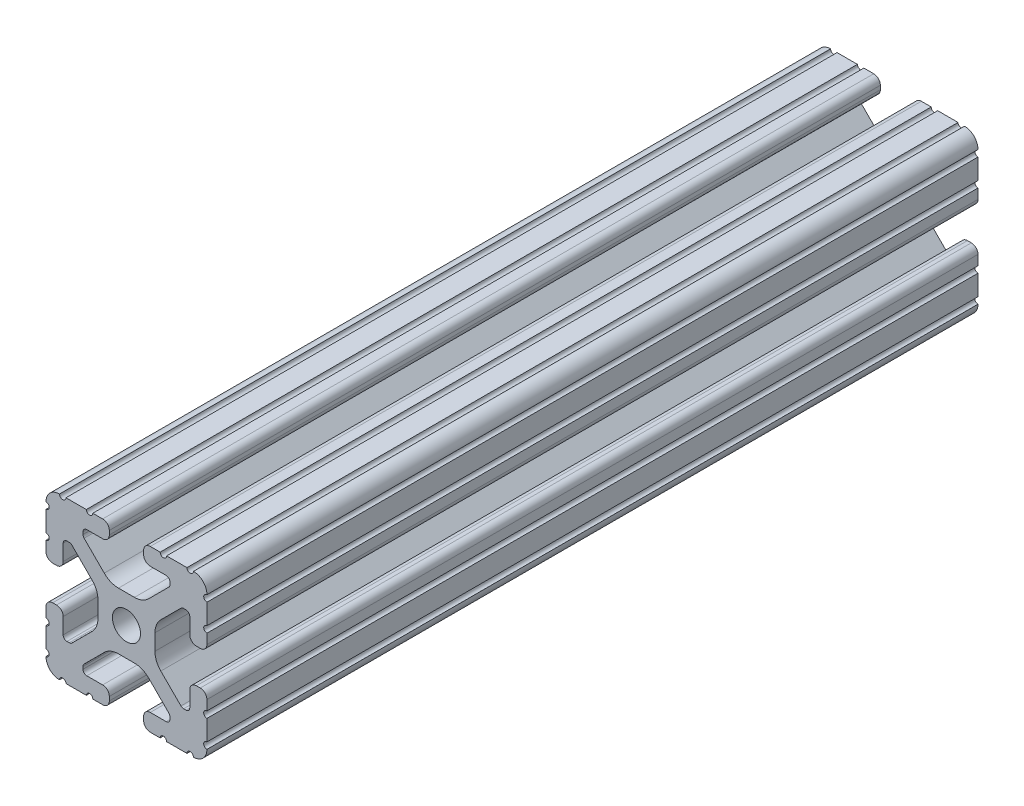
SolidWorks part; units mm, degrees
material "6105-T5 Aluminum"
ref_plane "Front Plane" through (0, 0, 0) normal (0, 0, 1) x (1, 0, 0)
ref_plane "Top Plane" through (0, 0, 0) normal (0, 1, 0) x (1, 0, 0)
ref_plane "Right Plane" through (0, 0, 0) normal (1, 0, 0) x (0, 0, -1)
sketch "Sketch1" plane through (0, 0, 0) normal (0, 0, 1) x (1, 0, 0)
  line L0 (-14.097, 10.287) -> (-13.5289, 10.287)
  line L1 (-12.9003, 10.0266) -> (-8.1292, 5.2555)
  line L2 (-6.738, 1.8969) -> (-6.738, -1.8969)
  line L3 (-8.1292, -5.2555) -> (-12.9003, -10.0266)
  line L4 (-13.5289, -10.287) -> (-14.097, -10.287)
  line L5 (-14.986, -9.398) -> (-14.986, -5.6388)
  line L6 (-16.5608, -4.064) -> (-17.4752, -4.064)
  line L7 (-19.05, -5.6388) -> (-19.05, -7.9756)
  line L8 (-19.05, -9.4996) -> (-19.05, -14.3256)
  line L9 (-19.05, -15.8496) -> (-19.05, -15.875)
  line L10 (-15.875, -19.05) -> (-15.8496, -19.05)
  line L11 (-14.3256, -19.05) -> (-9.4996, -19.05)
  line L12 (-7.9756, -19.05) -> (-5.6388, -19.05)
  line L13 (-4.064, -17.4752) -> (-4.064, -16.5608)
  line L14 (-5.6388, -14.986) -> (-9.398, -14.986)
  line L15 (-10.287, -14.097) -> (-10.287, -13.5289)
  line L16 (-10.0266, -12.9003) -> (-5.2555, -8.1292)
  line L17 (-1.8969, -6.738) -> (1.8969, -6.738)
  line L18 (5.2555, -8.1292) -> (10.0266, -12.9003)
  line L19 (10.287, -13.5289) -> (10.287, -14.097)
  line L20 (9.398, -14.986) -> (5.6388, -14.986)
  line L21 (4.064, -16.5608) -> (4.064, -17.4752)
  line L22 (5.6388, -19.05) -> (7.9756, -19.05)
  line L23 (9.4996, -19.05) -> (14.3256, -19.05)
  line L24 (15.8496, -19.05) -> (15.875, -19.05)
  line L25 (19.05, -15.875) -> (19.05, -15.8496)
  line L26 (19.05, -14.3256) -> (19.05, -9.4996)
  line L27 (19.05, -7.9756) -> (19.05, -5.6388)
  line L28 (17.4752, -4.064) -> (16.5608, -4.064)
  line L29 (14.986, -5.6388) -> (14.986, -9.398)
  line L30 (14.097, -10.287) -> (13.5289, -10.287)
  line L31 (12.9003, -10.0266) -> (8.1292, -5.2555)
  line L32 (6.738, -1.8969) -> (6.738, 1.8969)
  line L33 (8.1292, 5.2555) -> (12.9003, 10.0266)
  line L34 (13.5289, 10.287) -> (14.097, 10.287)
  line L35 (14.986, 9.398) -> (14.986, 5.6388)
  line L36 (16.5608, 4.064) -> (17.4752, 4.064)
  line L37 (19.05, 5.6388) -> (19.05, 7.9756)
  line L38 (19.05, 9.4996) -> (19.05, 14.3256)
  line L39 (19.05, 15.8496) -> (19.05, 15.875)
  line L40 (15.875, 19.05) -> (15.8496, 19.05)
  line L41 (14.3256, 19.05) -> (9.4996, 19.05)
  line L42 (7.9756, 19.05) -> (5.6388, 19.05)
  line L43 (4.064, 17.4752) -> (4.064, 16.5608)
  line L44 (5.6388, 14.986) -> (9.398, 14.986)
  line L45 (10.287, 14.097) -> (10.287, 13.5289)
  line L46 (10.0266, 12.9003) -> (5.2555, 8.1292)
  line L47 (1.8969, 6.738) -> (-1.8969, 6.738)
  line L48 (-5.2555, 8.1292) -> (-10.0266, 12.9003)
  line L49 (-10.287, 13.5289) -> (-10.287, 14.097)
  line L50 (-9.398, 14.986) -> (-5.6388, 14.986)
  line L51 (-4.064, 16.5608) -> (-4.064, 17.4752)
  line L52 (-5.6388, 19.05) -> (-7.9756, 19.05)
  line L53 (-9.4996, 19.05) -> (-14.3256, 19.05)
  line L54 (-15.8496, 19.05) -> (-15.875, 19.05)
  line L55 (-19.05, 15.875) -> (-19.05, 15.8496)
  line L56 (-19.05, 14.3256) -> (-19.05, 9.4996)
  line L57 (-19.05, 7.9756) -> (-19.05, 5.6388)
  line L58 (-17.4752, 4.064) -> (-16.5608, 4.064)
  line L59 (-14.986, 5.6388) -> (-14.986, 9.398)
  circle A0 centre (0, 0) radius 3.3274
  arc A1 (-14.097, 10.287) -> (-14.986, 9.398) centre (-14.097, 9.398) ccw
  arc A2 (-12.9003, 10.0266) -> (-13.5289, 10.287) centre (-13.5289, 9.398) ccw
  arc A3 (-6.738, 1.8969) -> (-8.1292, 5.2555) centre (-11.4878, 1.8969) ccw
  arc A4 (-8.1292, -5.2555) -> (-6.738, -1.8969) centre (-11.4878, -1.8969) ccw
  arc A5 (-13.5289, -10.287) -> (-12.9003, -10.0266) centre (-13.5289, -9.398) ccw
  arc A6 (-14.986, -9.398) -> (-14.097, -10.287) centre (-14.097, -9.398) ccw
  arc A7 (-14.986, -5.6388) -> (-16.5608, -4.064) centre (-16.5608, -5.6388) ccw
  arc A8 (-17.4752, -4.064) -> (-19.05, -5.6388) centre (-17.4752, -5.6388) ccw
  arc A9 (-19.05, -9.4996) -> (-19.05, -7.9756) centre (-19.05, -8.7376) ccw
  arc A10 (-19.05, -15.8496) -> (-19.05, -14.3256) centre (-19.05, -15.0876) ccw
  arc A11 (-19.05, -15.875) -> (-15.875, -19.05) centre (-15.875, -15.875) ccw
  arc A12 (-14.3256, -19.05) -> (-15.8496, -19.05) centre (-15.0876, -19.05) ccw
  arc A13 (-7.9756, -19.05) -> (-9.4996, -19.05) centre (-8.7376, -19.05) ccw
  arc A14 (-5.6388, -19.05) -> (-4.064, -17.4752) centre (-5.6388, -17.4752) ccw
  arc A15 (-4.064, -16.5608) -> (-5.6388, -14.986) centre (-5.6388, -16.5608) ccw
  arc A16 (-10.287, -14.097) -> (-9.398, -14.986) centre (-9.398, -14.097) ccw
  arc A17 (-10.0266, -12.9003) -> (-10.287, -13.5289) centre (-9.398, -13.5289) ccw
  arc A18 (-1.8969, -6.738) -> (-5.2555, -8.1292) centre (-1.8969, -11.4878) ccw
  arc A19 (5.2555, -8.1292) -> (1.8969, -6.738) centre (1.8969, -11.4878) ccw
  arc A20 (10.287, -13.5289) -> (10.0266, -12.9003) centre (9.398, -13.5289) ccw
  arc A21 (9.398, -14.986) -> (10.287, -14.097) centre (9.398, -14.097) ccw
  arc A22 (5.6388, -14.986) -> (4.064, -16.5608) centre (5.6388, -16.5608) ccw
  arc A23 (4.064, -17.4752) -> (5.6388, -19.05) centre (5.6388, -17.4752) ccw
  arc A24 (9.4996, -19.05) -> (7.9756, -19.05) centre (8.7376, -19.05) ccw
  arc A25 (15.8496, -19.05) -> (14.3256, -19.05) centre (15.0876, -19.05) ccw
  arc A26 (15.875, -19.05) -> (19.05, -15.875) centre (15.875, -15.875) ccw
  arc A27 (19.05, -14.3256) -> (19.05, -15.8496) centre (19.05, -15.0876) ccw
  arc A28 (19.05, -7.9756) -> (19.05, -9.4996) centre (19.05, -8.7376) ccw
  arc A29 (19.05, -5.6388) -> (17.4752, -4.064) centre (17.4752, -5.6388) ccw
  arc A30 (16.5608, -4.064) -> (14.986, -5.6388) centre (16.5608, -5.6388) ccw
  arc A31 (14.097, -10.287) -> (14.986, -9.398) centre (14.097, -9.398) ccw
  arc A32 (12.9003, -10.0266) -> (13.5289, -10.287) centre (13.5289, -9.398) ccw
  arc A33 (6.738, -1.8969) -> (8.1292, -5.2555) centre (11.4878, -1.8969) ccw
  arc A34 (8.1292, 5.2555) -> (6.738, 1.8969) centre (11.4878, 1.8969) ccw
  arc A35 (13.5289, 10.287) -> (12.9003, 10.0266) centre (13.5289, 9.398) ccw
  arc A36 (14.986, 9.398) -> (14.097, 10.287) centre (14.097, 9.398) ccw
  arc A37 (14.986, 5.6388) -> (16.5608, 4.064) centre (16.5608, 5.6388) ccw
  arc A38 (17.4752, 4.064) -> (19.05, 5.6388) centre (17.4752, 5.6388) ccw
  arc A39 (19.05, 9.4996) -> (19.05, 7.9756) centre (19.05, 8.7376) ccw
  arc A40 (19.05, 15.8496) -> (19.05, 14.3256) centre (19.05, 15.0876) ccw
  arc A41 (19.05, 15.875) -> (15.875, 19.05) centre (15.875, 15.875) ccw
  arc A42 (14.3256, 19.05) -> (15.8496, 19.05) centre (15.0876, 19.05) ccw
  arc A43 (7.9756, 19.05) -> (9.4996, 19.05) centre (8.7376, 19.05) ccw
  arc A44 (5.6388, 19.05) -> (4.064, 17.4752) centre (5.6388, 17.4752) ccw
  arc A45 (4.064, 16.5608) -> (5.6388, 14.986) centre (5.6388, 16.5608) ccw
  arc A46 (10.287, 14.097) -> (9.398, 14.986) centre (9.398, 14.097) ccw
  arc A47 (10.0266, 12.9003) -> (10.287, 13.5289) centre (9.398, 13.5289) ccw
  arc A48 (1.8969, 6.738) -> (5.2555, 8.1292) centre (1.8969, 11.4878) ccw
  arc A49 (-5.2555, 8.1292) -> (-1.8969, 6.738) centre (-1.8969, 11.4878) ccw
  arc A50 (-10.287, 13.5289) -> (-10.0266, 12.9003) centre (-9.398, 13.5289) ccw
  arc A51 (-9.398, 14.986) -> (-10.287, 14.097) centre (-9.398, 14.097) ccw
  arc A52 (-5.6388, 14.986) -> (-4.064, 16.5608) centre (-5.6388, 16.5608) ccw
  arc A53 (-4.064, 17.4752) -> (-5.6388, 19.05) centre (-5.6388, 17.4752) ccw
  arc A54 (-9.4996, 19.05) -> (-7.9756, 19.05) centre (-8.7376, 19.05) ccw
  arc A55 (-15.8496, 19.05) -> (-14.3256, 19.05) centre (-15.0876, 19.05) ccw
  arc A56 (-15.875, 19.05) -> (-19.05, 15.875) centre (-15.875, 15.875) ccw
  arc A57 (-19.05, 14.3256) -> (-19.05, 15.8496) centre (-19.05, 15.0876) ccw
  arc A58 (-19.05, 7.9756) -> (-19.05, 9.4996) centre (-19.05, 8.7376) ccw
  arc A59 (-19.05, 5.6388) -> (-17.4752, 4.064) centre (-17.4752, 5.6388) ccw
  arc A60 (-16.5608, 4.064) -> (-14.986, 5.6388) centre (-16.5608, 5.6388) ccw
extrude "Boss-Extrude1" add sketch "Sketch1" along normal blind 182.5625
